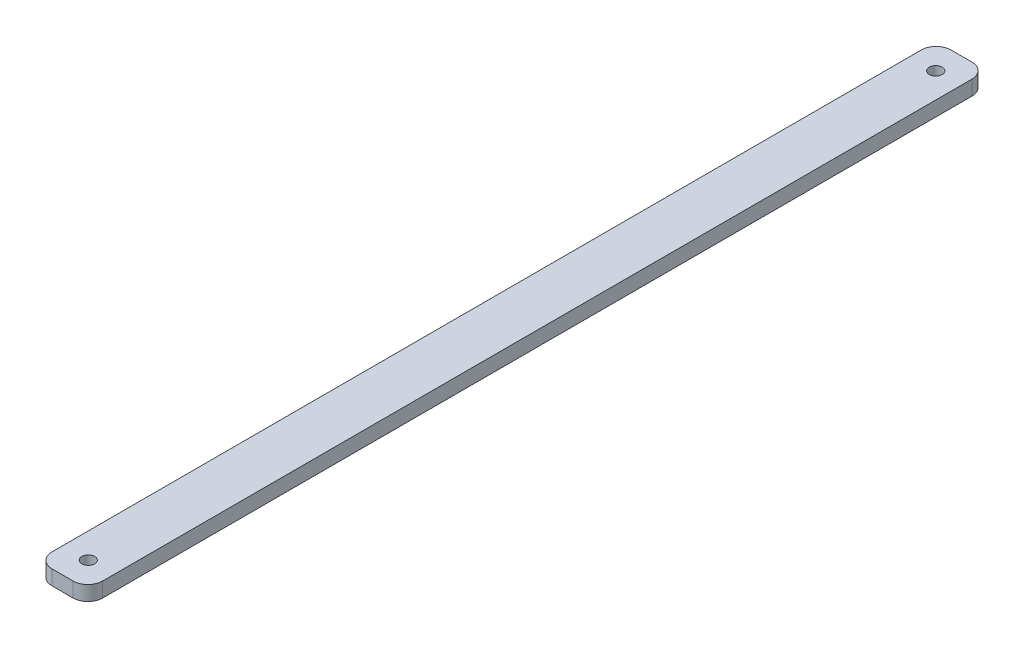
SolidWorks part; units mm, degrees
ref_plane "Front Plane" through (0, 0, 0) normal (0, 0, 1) x (1, 0, 0)
ref_plane "Top Plane" through (0, 0, 0) normal (0, 1, 0) x (1, 0, 0)
ref_plane "Right Plane" through (0, 0, 0) normal (1, 0, 0) x (0, 0, -1)
sketch "Sketch1" plane through (0, 0, 0) normal (0, 1, 0) x (1, 0, 0)
  line L0 (0, 83.82) -> (0, 0) construction
  line L1 (-5, 88.9) -> (5, 88.9)
  line L2 (-5, 88.9) -> (-5, -88.9)
  line L3 (-5, -88.9) -> (5, -88.9)
  line L4 (5, 88.9) -> (5, -88.9)
  line L5 (-5, 88.9) -> (5, -88.9) construction
  line L6 (-5, -88.9) -> (5, 88.9) construction
  line L7 (0, 0) -> (0, -83.82) construction
  circle A0 centre (0, 83.82) radius 1.27
  circle A1 centre (0, -83.82) radius 1.27
  point P1 (0, 0)
  dimension "D3" = 2.54
  dimension "D5" = 2.54
  dimension "D1" = 177.8
  dimension "D2" = 10
  dimension "D4" = 167.64
extrude "Boss-Extrude1" add sketch "Sketch1" along normal blind 2.921
fillet "Fillet1" radius 2.921 4 edges at (5, 1.4605, -88.9) (-5, 1.4605, -88.9) (-5, 1.4605, 88.9) (5, 1.4605, 88.9)
